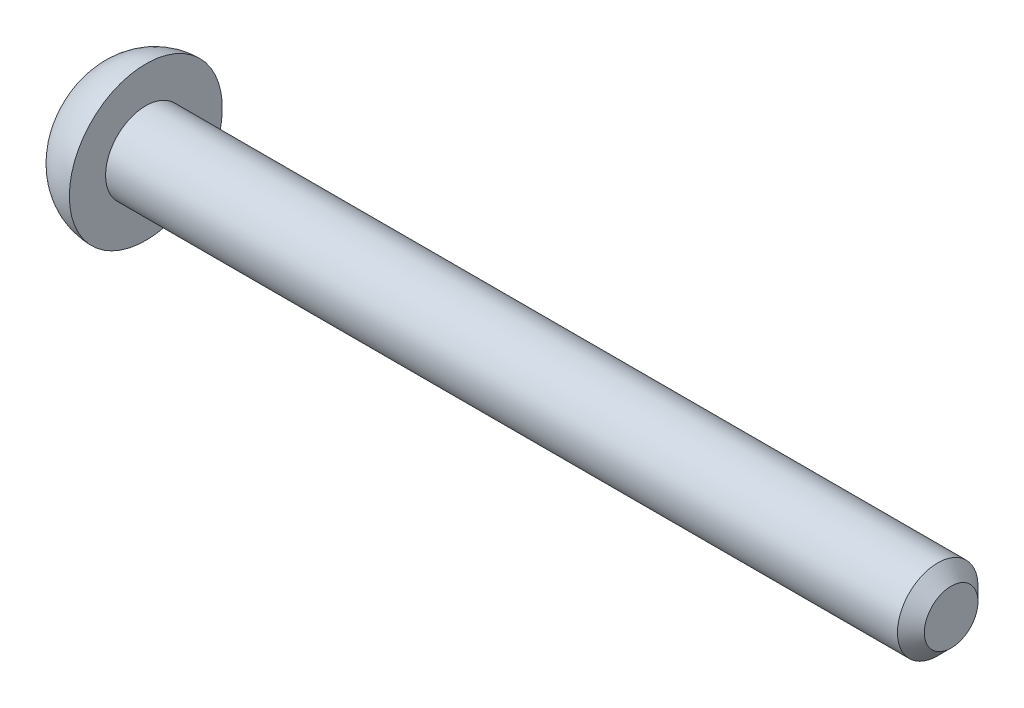
SolidWorks part; units mm, degrees
ref_plane "Front Plane" through (0, 0, 0) normal (0, 0, 1) x (1, 0, 0)
ref_plane "Top Plane" through (0, 0, 0) normal (0, 1, 0) x (1, 0, 0)
ref_plane "Right Plane" through (0, 0, 0) normal (1, 0, 0) x (0, 0, -1)
sketch "Sketch2" plane through (0, 0, 0) normal (0, 1, 0) x (1, 0, 0)
  line L0 (0, 0) -> (0, 1.5)
  line L1 (0, -3.135) -> (0, 3.135) construction
  line L2 (0, 1.5) -> (-30, 1.5)
  line L3 (-30, 1.5) -> (-30, 0) construction
  line L4 (-3.135, 0) -> (3.135, 0) construction
  line L5 (-31.65, 2.049) -> (-31.65, 0)
  line L6 (-31.65, 0) -> (0, 0)
  line L7 (-30, 2.85) -> (-30, 1.5)
  arc A0 (-31.65, 2.049) -> (-30, 2.85) centre (-30, 0.75) cw
  dimension "D2" = 30
  dimension "D3" = 2.85
  dimension "D1" = 1.65
  dimension "D4" = 1.5
revolve "Revolve1" add sketch "Sketch2" angle 360 about L6
chamfer "Chamfer1" distance 0.5 angle 45 1 edges at (0, 0, 1.5)
sketch "Sketch4" plane through (-31.65, 0, 0) normal (-1, 0, 0) x (0, 0, 1)
  line L1 (0.8389, 1.453) -> (-0.8389, 1.453) construction
  line L2 (-0.8389, 1.453) -> (-1.6778, 0) construction
  line L3 (-1.6778, 0) -> (-0.8389, -1.453) construction
  line L4 (-0.8389, -1.453) -> (0.8389, -1.453) construction
  line L5 (0.8389, -1.453) -> (1.6778, 0) construction
  line L6 (1.6778, 0) -> (0.8389, 1.453) construction
  circle A0 centre (0, 0) radius 1.453 construction
  arc A1 (-1.342, 0.0907) -> (-0.7496, 1.1169) centre (-1.7745, 1.0245) ccw
  arc A2 (-0.5924, 1.2076) -> (0.5924, 1.2076) centre (0, 2.049) ccw
  arc A3 (0.7496, 1.1169) -> (1.342, 0.0907) centre (1.7745, 1.0245) ccw
  arc A4 (1.342, -0.0907) -> (0.7496, -1.1169) centre (1.7745, -1.0245) ccw
  arc A5 (-0.5924, -1.2076) -> (0.5924, -1.2076) centre (0, -2.049) cw
  arc A6 (-0.7496, -1.1169) -> (-1.342, -0.0907) centre (-1.7745, -1.0245) ccw
  circle A7 centre (0, 0) radius 2.049 construction
  arc A8 (0.7496, 1.1169) -> (0.5924, 1.2076) centre (0.65, 1.1258) ccw
  arc A9 (1.342, -0.0907) -> (1.342, 0.0907) centre (1.3, 0) ccw
  arc A10 (0.7496, -1.1169) -> (0.5924, -1.2076) centre (0.65, -1.1258) cw
  arc A11 (-0.7496, -1.1169) -> (-0.5924, -1.2076) centre (-0.65, -1.1258) ccw
  arc A12 (-1.342, 0.0907) -> (-1.342, -0.0907) centre (-1.3, 0) ccw
  arc A13 (-0.7496, 1.1169) -> (-0.5924, 1.2076) centre (-0.65, 1.1258) cw
  circle A14 centre (0, 0) radius 2.049 construction
  point P40 (2.049, 0)
  dimension "D1" = 0.1
  dimension "D2" = 2.6
extrude "Cut-Extrude1" cut sketch "Sketch4" against normal blind 1
equation "\"d1\"= 3"
equation "\"l\"= 30"
equation "\"d2\"= 5.7"
equation "\"t\"= 1"
equation "\"k\"=1.65"
equation "\"A\"=2.8"
equation "\"D3@Sketch2\"=\"d2\" / 2"
equation "\"D1@Sketch2\"= \"k\""
equation "\"D4@Sketch2\"=\"d1\" / 2"
equation "\"D2@Sketch4\"= \"A\" - 2 * \"D1@Sketch4\""
equation "\"D1@Cut-Extrude1\"= \"t\""
equation "\"D2@Sketch2\"=\"l\""
